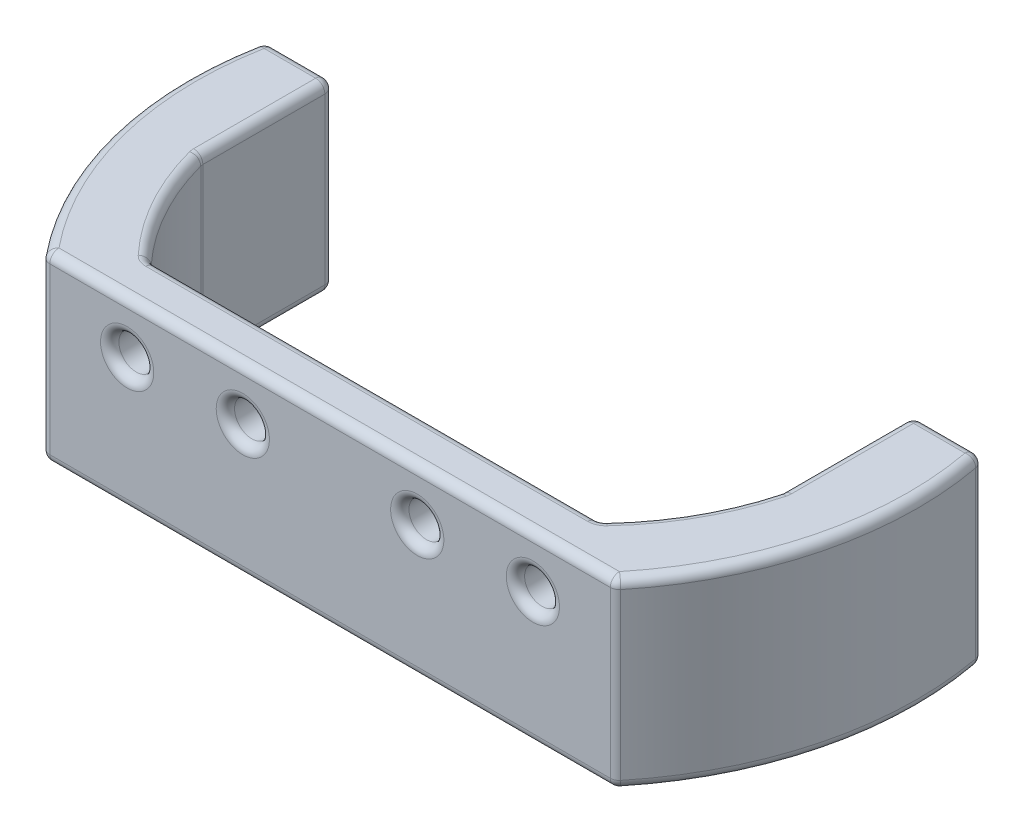
SolidWorks part; units mm, degrees
ref_plane "Front Plane" through (0, 0, 0) normal (0, 0, 1) x (1, 0, 0)
ref_plane "Top Plane" through (0, 0, 0) normal (0, 1, 0) x (1, 0, 0)
ref_plane "Right Plane" through (0, 0, 0) normal (1, 0, 0) x (0, 0, -1)
sketch "Sketch1" plane through (0, 0, 0) normal (0, 1, 0) x (1, 0, 0)
  line L0 (0, 0) -> (99.06, 0) construction
  line L1 (10.16, -40.64) -> (88.9, -40.64)
  line L2 (0, 0) -> (9.4432, 0)
  line L3 (18.415, -34.29) -> (80.645, -34.29)
  line L4 (89.6168, 0) -> (99.06, 0)
  line L5 (49.53, 0) -> (49.53, -40.64) construction
  line L6 (0, 14.2488) -> (0, -35.612) construction
  line L7 (-3.039, -40.64) -> (123.3757, -40.64) construction
  line L8 (99.06, 17.0692) -> (99.06, -34.8061) construction
  line L9 (0, 36.4335) -> (0, -77.3846) construction
  line L10 (99.06, 36.4335) -> (99.06, -77.3846) construction
  line L11 (88.9, -40.64) -> (99.06, 0) construction
  line L12 (0, 0) -> (10.16, -40.64) construction
  line L13 (44.45, -9.1594) -> (46.99, -9.8425) construction
  line L14 (9.4432, -18.3187) -> (9.4432, 0)
  line L15 (52.07, -9.8425) -> (54.61, -9.1594) construction
  line L16 (89.6168, -18.3187) -> (89.6168, 0)
  arc A0 (0, 0) -> (10.16, -40.64) centre (46.99, -9.8425) ccw
  arc A1 (99.06, 0) -> (88.9, -40.64) centre (52.07, -9.8425) cw
  arc A2 (9.4432, 0) -> (18.415, -34.29) centre (44.45, -9.1594) ccw construction
  arc A3 (80.645, -34.29) -> (89.6168, 0) centre (54.61, -9.1594) ccw construction
  arc A4 (9.4432, -18.3187) -> (18.415, -34.29) centre (44.45, -9.1594) ccw
  arc A5 (89.6168, -18.3187) -> (80.645, -34.29) centre (54.61, -9.1594) cw
  point P14 (49.53, -34.29)
  point P26 (99.06, -40.64)
  point P27 (99.06, -40.64)
  point P28 (0, -40.64)
  dimension "D4" = 62.23
  dimension "D5" = 10.16
  dimension "D7" = 5.08
  dimension "D8" = 41.8908
  dimension "D9" = 10.16
  dimension "D1" = 99.06
  dimension "D2" = 9.4432
  dimension "D3" = 6.35
  dimension "D6" = 40.64
extrude "Boss-Extrude1" add sketch "Sketch1" along normal blind 25.4
sketch "Sketch2" plane through (0, 0, 34.29) normal (0, 0, -1) x (-1, 0, 0)
  line L0 (-80.645, 18.288) -> (-18.415, 18.288) construction
  line L1 (-80.645, 25.4) -> (-80.645, 0) construction
  line L2 (-18.415, 25.4) -> (-18.415, 0) construction
  line L3 (-80.645, 18.288) -> (-77.597, 18.288) construction
  line L4 (-21.463, 18.288) -> (-18.415, 18.288) construction
  circle A0 centre (-77.597, 18.288) radius 2.413
  circle A3 centre (-21.463, 18.288) radius 2.413
  circle A4 centre (-61.595, 18.288) radius 2.413
  circle A5 centre (-37.465, 18.288) radius 2.413
  dimension "D1" = 4.826
  dimension "D3" = 3.048
  dimension "D2" = 56.134
  dimension "D4" = 16.002
  dimension "D5" = 16.002
  dimension "D6" = 7.112
extrude "Cut-Extrude1" cut sketch "Sketch2" against normal through all
sketch "Sketch3" plane through (0, 0, 0) normal (0, 0, -1) x (-1, 0, 0)
  line L0 (-9.4432, 5.08) -> (0, 5.08) construction
  line L1 (0, 25.4) -> (0, 0) construction
  line L2 (-9.4432, 25.4) -> (-9.4432, 0) construction
  line L3 (-4.7216, 25.4) -> (-4.7216, -15.24) construction
  line L4 (-9.4432, 25.4) -> (0, 25.4) construction
  line L6 (-6.4814, 8.128) -> (-2.9618, 8.128)
  line L7 (-2.9618, 8.128) -> (-1.2021, 5.08)
  line L8 (-1.2021, 5.08) -> (-2.9618, 2.032)
  line L9 (-6.4814, 2.032) -> (-2.9618, 2.032)
  line L10 (-6.4814, 8.128) -> (-8.2411, 5.08)
  line L11 (-8.2411, 5.08) -> (-6.4814, 2.032)
  line L12 (-8.2411, 5.08) -> (-1.2021, 5.08)
  line L13 (-4.7216, 5.08) -> (-4.7216, 2.032)
  line L14 (-4.7216, 8.128) -> (-4.7216, 2.032)
  circle A0 centre (-4.7216, 5.08) radius 1.905
  point P17 (-4.7216, 8.128)
  point P22 (-4.7216, 2.032)
  point P26 (-4.7216, 5.08)
  point P28 (-4.7216, 5.08)
  dimension "D1" = 3.81
  dimension "D2" = 6.096
  dimension "D3" = 6.096
  dimension "D4" = 5.08
sketch "Sketch4" plane through (0, 0, 0) normal (0, 0, -1) x (-1, 0, 0)
  line L0 (-99.06, 5.08) -> (-89.6168, 5.08) construction
  line L3 (-94.3384, 25.4) -> (-94.3384, 0) construction
  line L6 (-92.5786, 2.032) -> (-96.0982, 2.032)
  line L7 (-96.0982, 2.032) -> (-97.8579, 5.08)
  line L8 (-97.8579, 5.08) -> (-96.0982, 8.128)
  line L9 (-92.5786, 8.128) -> (-96.0982, 8.128)
  line L10 (-92.5786, 2.032) -> (-90.8189, 5.08)
  line L11 (-90.8189, 5.08) -> (-92.5786, 8.128)
  line L12 (-94.3384, 8.128) -> (-94.3384, 2.032)
  line L13 (-97.8579, 5.08) -> (-90.8189, 5.08) construction
  line L14 (-99.06, 25.4) -> (-89.6168, 25.4) construction
  line L15 (-99.06, 0) -> (-89.6168, 0) construction
  circle A0 centre (-94.3384, 5.08) radius 1.905
  point P17 (-94.3384, 2.032)
  point P21 (-94.3384, 8.128)
  point P25 (-94.3384, 5.08)
  point P28 (-94.3384, 5.08)
  point P31 (-94.3384, 8.128)
  point P34 (-94.3384, 2.032)
  dimension "D1" = 3.81
  dimension "D2" = 6.096
  dimension "D3" = 6.096
  dimension "D4" = 5.08
extrude "Cut-Extrude3" cut sketch "Sketch4" against normal blind 1.7526 draft 8 contours A0
extrude "Cut-Extrude4" cut sketch "Sketch3" against normal blind 1.7526 draft 8 contours A0
sketch "Sketch10" plane through (0, 0, 40.64) normal (0, 0, 1) x (1, 0, 0)
  line L0 (19.7032, 21.336) -> (23.2228, 21.336)
  line L1 (23.2228, 21.336) -> (24.9825, 18.288)
  line L2 (24.9825, 18.288) -> (23.2228, 15.24)
  line L3 (23.2228, 15.24) -> (19.7032, 15.24)
  line L4 (19.7032, 15.24) -> (17.9435, 18.288)
  line L5 (17.9435, 18.288) -> (19.7032, 21.336)
  line L6 (21.463, 21.336) -> (21.463, 15.24) construction
  line L7 (24.9825, 18.288) -> (17.9435, 18.288) construction
  line L8 (35.7052, 21.336) -> (39.2248, 21.336)
  line L9 (39.2248, 21.336) -> (40.9845, 18.288)
  line L10 (40.9845, 18.288) -> (39.2248, 15.24)
  line L11 (39.2248, 15.24) -> (35.7052, 15.24)
  line L12 (35.7052, 15.24) -> (33.9455, 18.288)
  line L13 (33.9455, 18.288) -> (35.7052, 21.336)
  line L14 (37.465, 21.336) -> (37.465, 15.24) construction
  line L15 (40.9845, 18.288) -> (33.9455, 18.288) construction
  line L16 (59.8352, 21.336) -> (63.3548, 21.336)
  line L17 (63.3548, 21.336) -> (65.1145, 18.288)
  line L18 (65.1145, 18.288) -> (63.3548, 15.24)
  line L19 (63.3548, 15.24) -> (59.8352, 15.24)
  line L20 (59.8352, 15.24) -> (58.0755, 18.288)
  line L21 (58.0755, 18.288) -> (59.8352, 21.336)
  line L22 (61.595, 21.336) -> (61.595, 15.24) construction
  line L23 (65.1145, 18.288) -> (58.0755, 18.288) construction
  line L24 (75.8372, 21.336) -> (79.3568, 21.336)
  line L25 (79.3568, 21.336) -> (81.1165, 18.288)
  line L26 (81.1165, 18.288) -> (79.3568, 15.24)
  line L27 (79.3568, 15.24) -> (75.8372, 15.24)
  line L28 (75.8372, 15.24) -> (74.0775, 18.288)
  line L29 (74.0775, 18.288) -> (75.8372, 21.336)
  line L30 (77.597, 21.336) -> (77.597, 15.24) construction
  line L31 (74.0775, 18.288) -> (81.1165, 18.288) construction
  point P8 (21.463, 18.288)
  point P9 (37.465, 18.288)
  point P10 (61.595, 18.288)
  point P13 (77.597, 18.288)
  point P15 (21.463, 18.288)
  point P25 (37.465, 18.288)
  point P26 (61.595, 18.288)
  point P27 (77.597, 18.288)
  point P44 (77.597, 18.288)
  point P45 (81.1255, -1.736)
  dimension "D1" = 6.096
  dimension "D2" = 6.096
  dimension "D3" = 6.096
  dimension "D4" = 6.096
  dimension "D5" = 6.096
  dimension "D6" = 6.096
  dimension "D7" = 6.096
  dimension "D8" = 6.096
  dimension "D9" = 6.096
extrude "Cut-Extrude5" [suppressed] cut sketch "Sketch10" against normal blind 2.3368
fillet "Fillet1" [suppressed] radius 0.254
ref_plane "Plane1" through (99.06, 0, 0) normal (1, 0, 0) x (0, 0, -1)
fillet "Fillet6" radius 1.27 34 edges at (18.415, 12.7, 34.29) (9.4432, 12.7, 18.3187) (88.9, 12.7, 40.64) (49.53, 0, 40.64) (98.6463, 0, 21.4866) (49.53, 0, 34.29) (12.9017, 0, 26.8815) (9.4432, 0, 9.1594) (80.645, 12.7, 34.29) (86.1583, 0, 26.8815) (89.6168, 12.7, 18.3187) (89.6168, 0, 9.1594) (99.06, 12.7, 0) (89.6168, 12.7, 0) (94.3384, 0, 0) (9.4432, 12.7, 0) (4.7216, 0, 0) (0, 12.7, 0) (10.16, 12.7, 40.64) (0.4137, 0, 21.4866) (4.7216, 25.4, 0) (9.4432, 25.4, 9.1594) (12.9017, 25.4, 26.8815) (49.53, 25.4, 34.29) (86.1583, 25.4, 26.8815) (89.6168, 25.4, 9.1594) (94.3384, 25.4, 0) (98.6463, 25.4, 21.4866) (49.53, 25.4, 40.64) (0.4137, 25.4, 21.4866) (19.05, 18.288, 40.64) (35.052, 18.288, 40.64) (59.182, 18.288, 40.64) (75.184, 18.288, 40.64)
fillet "Fillet7" radius 0.254 6 edges at (75.184, 18.288, 34.29) (59.182, 18.288, 34.29) (35.052, 18.288, 34.29) (19.05, 18.288, 34.29) (2.8166, 5.08, 0) (92.4334, 5.08, 0)
